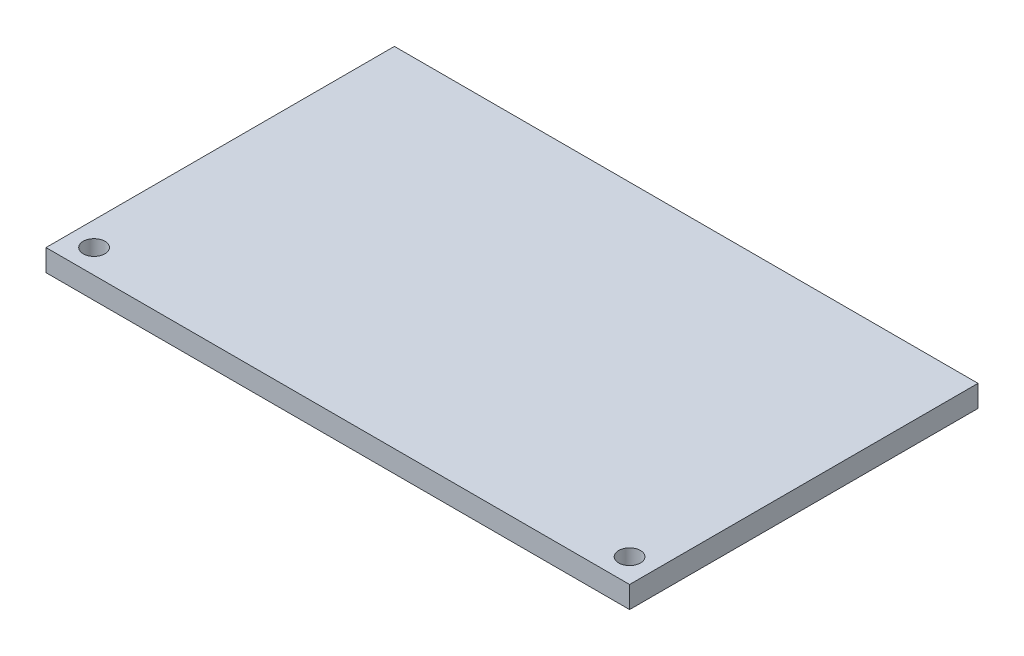
SolidWorks part; units mm, degrees
ref_plane "Front Plane" through (0, 0, 0) normal (0, 0, 1) x (1, 0, 0)
ref_plane "Top Plane" through (0, 0, 0) normal (0, 1, 0) x (1, 0, 0)
ref_plane "Right Plane" through (0, 0, 0) normal (1, 0, 0) x (0, 0, -1)
sketch "Sketch1" plane through (0, 0, 0) normal (0, 1, 0) x (1, 0, 0)
  line L1 (0, 0) -> (85.09, 0)
  line L2 (0, 0) -> (0, 50.8)
  line L3 (0, 50.8) -> (85.09, 50.8)
  line L4 (85.09, 0) -> (85.09, 50.8)
  circle A0 centre (3.5052, 3.5052) radius 1.5875
  circle A1 centre (81.5848, 3.5052) radius 1.5875
  dimension "D3" = 3.175
  dimension "D1" = 85.09
  dimension "D2" = 50.8
  dimension "D4" = 3.5052
  dimension "D5" = 3.5052
  dimension "D6" = 3.5052
extrude "Boss-Extrude1" add sketch "Sketch1" along normal blind 3.175
